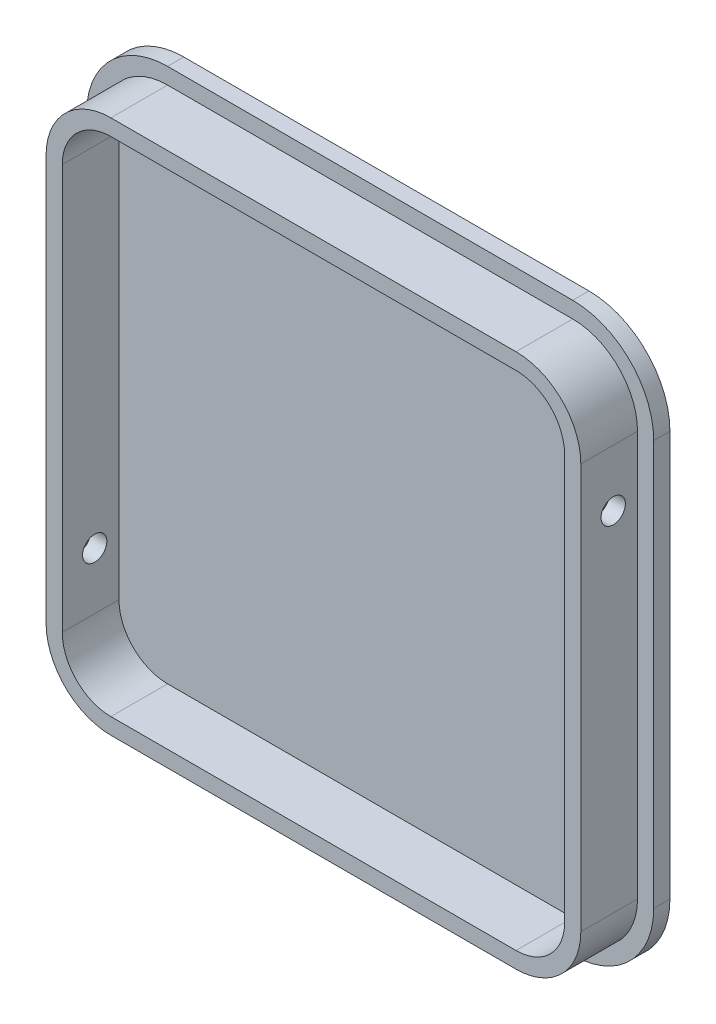
SolidWorks part; units mm, degrees
ref_plane "前视基准面" through (0, 0, 0) normal (0, 0, 1) x (1, 0, 0)
ref_plane "上视基准面" through (0, 0, 0) normal (0, 1, 0) x (1, 0, 0)
ref_plane "右视基准面" through (0, 0, 0) normal (1, 0, 0) x (0, 0, -1)
sketch "草图1" plane through (0, 0, 0) normal (0, 0, 1) x (1, 0, 0)
  line L1 (-23.1085, 22.918) -> (26.8915, 22.918)
  line L2 (-33.1085, 12.918) -> (-33.1085, -37.082)
  line L3 (-23.1085, -47.082) -> (26.8915, -47.082)
  line L4 (36.8915, 12.918) -> (36.8915, -37.082)
  arc A0 (-33.1085, 12.918) -> (-23.1085, 22.918) centre (-23.1085, 12.918) cw
  arc A1 (36.8915, 12.918) -> (26.8915, 22.918) centre (26.8915, 12.918) ccw
  arc A2 (26.8915, -47.082) -> (36.8915, -37.082) centre (26.8915, -37.082) ccw
  arc A3 (-23.1085, -47.082) -> (-33.1085, -37.082) centre (-23.1085, -37.082) cw
  point P6 (-33.1085, 22.918)
  point P9 (36.8915, 22.918)
  point P12 (36.8915, -47.082)
  dimension "D3" = 10
  dimension "D4" = 10
  dimension "D5" = 10
  dimension "D6" = 10
  dimension "D1" = 70
  dimension "D2" = 70
extrude "凸台-拉伸1" add sketch "草图1" along normal blind 2
sketch "草图2" plane through (0, 0, 2) normal (0, 0, 1) x (1, 0, 0)
  line L0 (26.8915, 22.918) -> (-23.1085, 22.918) construction
  line L1 (-23.1085, 20.918) -> (26.8915, 20.918)
  line L2 (-31.1085, 12.918) -> (-31.1085, -37.082)
  line L3 (-23.1085, -45.082) -> (26.8915, -45.082)
  line L4 (34.8915, 12.918) -> (34.8915, -37.082)
  line L5 (-33.1085, 12.918) -> (-33.1085, -37.082) construction
  line L6 (36.8915, -37.082) -> (36.8915, 12.918) construction
  line L7 (-23.1085, -47.082) -> (26.8915, -47.082) construction
  arc A0 (-31.1085, 12.918) -> (-23.1085, 20.918) centre (-23.1085, 12.918) cw
  arc A1 (34.8915, 12.918) -> (26.8915, 20.918) centre (26.8915, 12.918) ccw
  arc A2 (-23.1085, -45.082) -> (-31.1085, -37.082) centre (-23.1085, -37.082) cw
  arc A3 (26.8915, -45.082) -> (34.8915, -37.082) centre (26.8915, -37.082) ccw
  dimension "D5" = 8
  dimension "D6" = 8
  dimension "D7" = 8
  dimension "D8" = 8
  dimension "D1" = 2
  dimension "D2" = 2
  dimension "D3" = 2
  dimension "D4" = 2
extrude "凸台-拉伸2" add sketch "草图2" along normal blind 7
shell "抽壳1" thickness 2
sketch "草图3" plane through (-31.1085, 0, 0) normal (-1, 0, 0) x (0, 0, 1)
  line L0 (2, 12.918) -> (2, -37.082) construction
  line L2 (9, -37.082) -> (2, -37.082) construction
  circle A0 centre (5, -30.082) radius 1.5
  dimension "D1" = 3
  dimension "D2" = 7
extrude "切除-拉伸1" cut sketch "草图3" against normal blind 7
sketch "草图4" plane through (34.8915, 0, 0) normal (1, 0, 0) x (0, 0, -1)
  line L0 (-2, -37.082) -> (-2, 12.918) construction
  line L1 (-9, 12.918) -> (-2, 12.918) construction
  circle A0 centre (-5, 5.918) radius 1.5
  dimension "D1" = 3
  dimension "D2" = 7
extrude "切除-拉伸2" cut sketch "草图4" against normal blind 7
